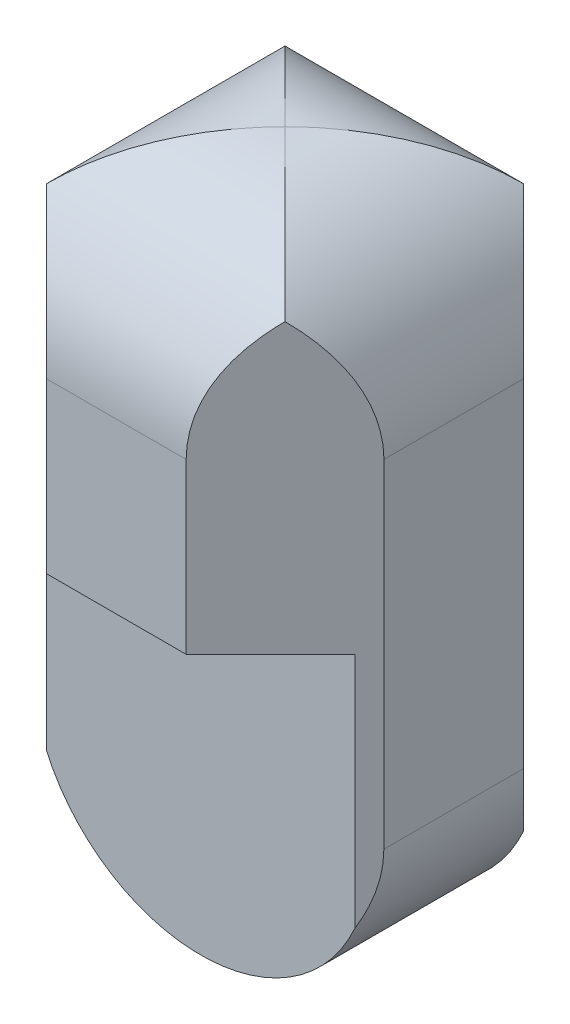
SolidWorks part; units mm, degrees
ref_plane "Front" through (0, 0, 0) normal (0, 0, 1) x (1, 0, 0)
ref_plane "Top" through (0, 0, 0) normal (0, 1, 0) x (1, 0, 0)
ref_plane "Right" through (0, 0, 0) normal (1, 0, 0) x (0, 0, -1)
sketch "草图1" plane through (0, 0, 0) normal (0, 1, 0) x (1, 0, 0)
  line L0 (-12.6518, 0) -> (13.462, 0) construction
  line L1 (0, 11.6722) -> (0, -14.1269) construction
  line L3 (10, 4.1421) -> (4.1421, 10)
  line L4 (4.1421, 10) -> (-4.1421, 10)
  line L5 (-4.1421, 10) -> (-10, 4.1421)
  line L6 (-10, 4.1421) -> (-10, -4.1421)
  line L7 (-10, -4.1421) -> (-4.1421, -10)
  line L8 (-4.1421, -10) -> (4.1421, -10)
  line L9 (4.1421, -10) -> (10, -4.1421)
  line L10 (10, -4.1421) -> (10, 4.1421)
  circle A0 centre (0, 0) radius 10 construction
extrude "凸台-拉伸1" add sketch "草图1" along normal blind 48
sketch "草图2" plane through (0, 0, 10) normal (0, 0, 1) x (1, 0, 0)
  line L0 (0, 0) -> (0, 24) construction
  line L7 (-10, 10) -> (-10, -2.3893)
  line L8 (-10, -2.3893) -> (10, -2.3893)
  line L9 (10, 10) -> (10, -2.3893)
  arc A1 (-10, 10) -> (10, 10) centre (0, 10) ccw
extrude "切除-拉伸1" cut sketch "草图2" against normal blind 66
sketch "草图4" plane through (0, 0, 10) normal (0, 0, 1) x (1, 0, 0)
  line L0 (10, 48) -> (10, 10) construction
  line L2 (-10, 10) -> (-10, 20)
  line L3 (-10, 20) -> (10, 20)
  line L4 (10, 10) -> (10, 20)
  arc A0 (-10, 10) -> (10, 10) centre (0, 10) ccw
extrude "切除-拉伸2" cut sketch "草图4" against normal blind 5
sketch "草图5" plane through (0, 0, -10) normal (0, 0, -1) x (-1, 0, 0)
  line L0 (10, 48) -> (10, 10) construction
  line L2 (-10, 10) -> (-10, 20)
  line L3 (-10, 20) -> (10, 20)
  line L4 (10, 10) -> (10, 20)
  arc A0 (-10, 10) -> (10, 10) centre (0, 10) ccw
extrude "切除-拉伸3" cut sketch "草图5" against normal blind 5
sketch "草图7" plane through (0, 0, 10) normal (0, 0, 1) x (1, 0, 0)
  line L0 (0, 48) -> (0, 0) construction
  line L1 (-4.1421, 48) -> (4.1421, 48) construction
  line L4 (-10, 30) -> (-10, 50.9406)
  line L5 (-10, 50.9406) -> (10, 50.9406)
  line L6 (10, 30) -> (10, 50.9406)
  arc A0 (10, 30) -> (-10, 30) centre (0, 30) ccw
extrude "切除-拉伸5" cut sketch "草图7" against normal blind 30
sketch "草图8" plane through (10, 0, 0) normal (1, 0, 0) x (0, 0, -1)
  line L0 (0, 40) -> (0, 0) construction
  line L1 (10, 40) -> (-10, 40) construction
  line L4 (-10, 30) -> (-10, 44.0756)
  line L5 (-10, 44.0756) -> (10, 44.0756)
  line L6 (10, 30) -> (10, 44.0756)
  arc A0 (10, 30) -> (-10, 30) centre (0, 30) ccw
  dimension "D1" = 10
extrude "切除-拉伸6" cut sketch "草图8" against normal blind 30
